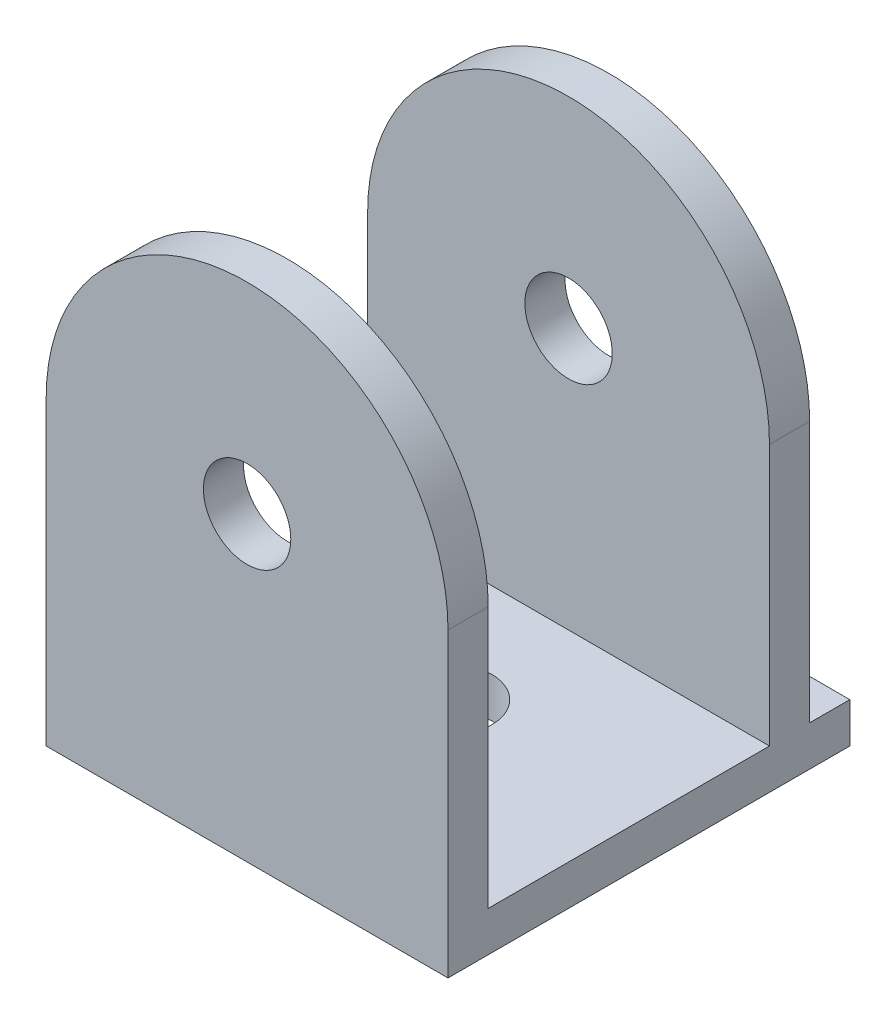
SolidWorks part; units mm, degrees
ref_plane "Front Plane" through (0, 0, 0) normal (0, 0, 1) x (1, 0, 0)
ref_plane "Top Plane" through (0, 0, 0) normal (0, 1, 0) x (1, 0, 0)
ref_plane "Right Plane" through (0, 0, 0) normal (1, 0, 0) x (0, 0, -1)
sketch "Sketch1" plane through (0, 0, 0) normal (0, 0, 1) x (1, 0, 0)
  line L0 (0, 0) -> (0, 41.3703) construction
  line L2 (-20, 30) -> (20, 30)
  line L3 (-20, 30) -> (-20, 0)
  line L4 (-20, 0) -> (20, 0)
  line L5 (20, 30) -> (20, 0)
  line L6 (-20, 30) -> (20, 0) construction
  line L7 (-20, 0) -> (20, 30) construction
  arc A0 (-20, 30) -> (20, 30) centre (0, 30) cw
  point P3 (0, 15)
  dimension "D1" = 30
  dimension "D2" = 40
extrude "Boss-Extrude1" add sketch "Sketch1" along normal mid plane 40 contours A0 L2 | L5 L2 L3 L4
sketch "Sketch2" plane through (0, 0, 0) normal (1, 0, 0) x (0, 0, -1)
  line L0 (-20, 0) -> (20, 0) construction
  line L1 (-16, 50) -> (12, 50)
  line L2 (-16, 50) -> (-16, 4)
  line L3 (-16, 4) -> (12, 4)
  line L4 (12, 50) -> (12, 4)
  line L5 (20, 50) -> (16, 50)
  line L6 (20, 50) -> (20, 4)
  line L7 (20, 4) -> (16, 4)
  line L8 (16, 50) -> (16, 4)
  line L9 (20, 50) -> (-20, 50) construction
  line L10 (-20, 50) -> (-20, 30) construction
  dimension "D1" = 4
  dimension "D2" = 4
  dimension "D3" = 4
  dimension "D4" = 4
  dimension "D5" = 4
extrude "Cut-Extrude1" cut sketch "Sketch2" against normal through all both and the other way through all
sketch "Sketch3" plane through (0, 0, 20) normal (0, 0, 1) x (1, 0, 0)
  arc A0 (20, 30) -> (-20, 30) centre (0, 30) ccw construction
  arc A1 (20, 30) -> (-20, 30) centre (0, 30) ccw
  circle A2 centre (0, 30) radius 4.35
  dimension "D1" = 8.7
extrude "Cut-Extrude2" cut sketch "Sketch3" against normal through all and the other way through all contours A2
sketch "Sketch4" plane through (0, 0, 0) normal (0, -1, 0) x (1, 0, 0)
  circle A0 centre (0, 0) radius 4.35
  dimension "D1" = 8.7
extrude "Cut-Extrude3" cut sketch "Sketch4" against normal through all
